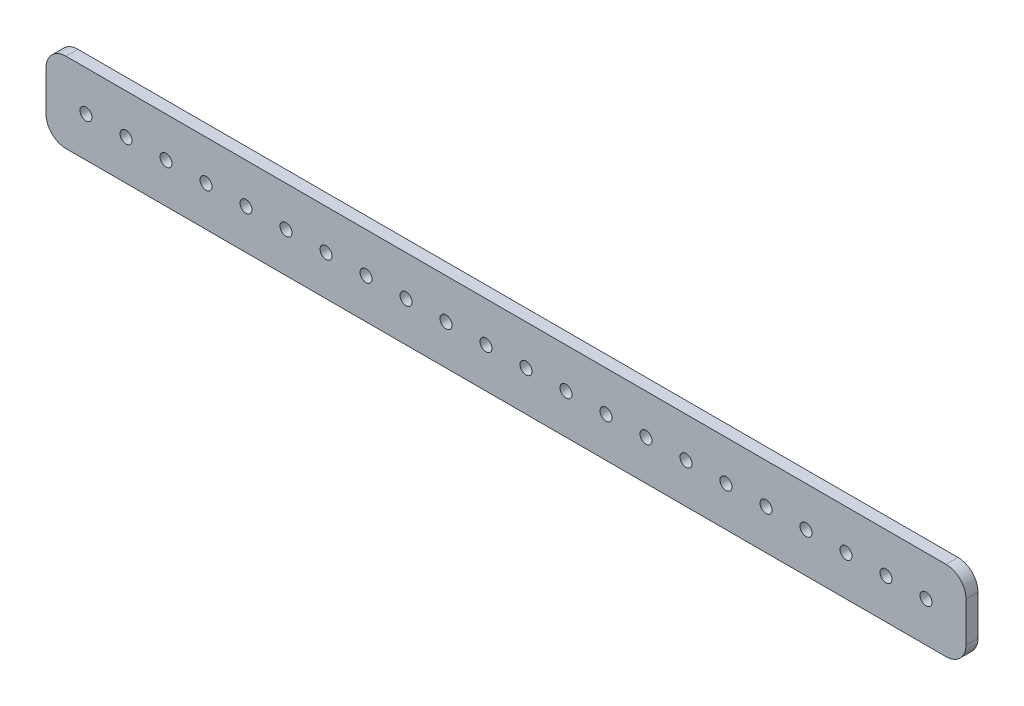
SolidWorks part; units mm, degrees
material "Maple"
ref_plane "Front Plane" through (0, 0, 0) normal (0, 0, 1) x (1, 0, 0)
ref_plane "Top Plane" through (0, 0, 0) normal (0, 1, 0) x (1, 0, 0)
ref_plane "Right Plane" through (0, 0, 0) normal (1, 0, 0) x (0, 0, -1)
sketch "Sketch1" plane through (0, 0, 0) normal (0, 0, 1) x (1, 0, 0)
  line L1 (-110, 10) -> (110, 10)
  line L2 (-115, 5) -> (-115, -5)
  line L3 (-110, -10) -> (110, -10)
  line L4 (115, 5) -> (115, -5)
  line L5 (-115, 10) -> (115, -10) construction
  line L6 (-115, -10) -> (115, 10) construction
  line L50 (-115, 0) -> (-105, 0) construction
  line L51 (-105, 0) -> (-95, 0) construction
  line L52 (-95, 0) -> (-85, 0) construction
  line L53 (-85, 0) -> (-75, 0) construction
  line L54 (-75, 0) -> (-65, 0) construction
  line L55 (-65, 0) -> (-55, 0) construction
  line L56 (-55, 0) -> (-45, 0) construction
  line L57 (-45, 0) -> (-35, 0) construction
  line L58 (-35, 0) -> (-25, 0) construction
  line L59 (-25, 0) -> (-15, 0) construction
  line L60 (-15, 0) -> (-5, 0) construction
  line L61 (-5, 0) -> (5, 0) construction
  line L62 (5, 0) -> (15, 0) construction
  line L63 (15, 0) -> (25, 0) construction
  line L64 (25, 0) -> (35, 0) construction
  line L65 (35, 0) -> (45, 0) construction
  line L66 (45, 0) -> (55, 0) construction
  line L67 (55, 0) -> (65, 0) construction
  line L68 (65, 0) -> (75, 0) construction
  line L69 (75, 0) -> (85, 0) construction
  line L70 (85, 0) -> (95, 0) construction
  line L71 (95, 0) -> (105, 0) construction
  arc A21 (115, -5) -> (110, -10) centre (110, -5) cw
  arc A22 (115, 5) -> (110, 10) centre (110, 5) ccw
  arc A23 (-110, -10) -> (-115, -5) centre (-110, -5) cw
  arc A24 (-110, 10) -> (-115, 5) centre (-110, 5) ccw
  circle A46 centre (-105, 0) radius 1.5
  circle A47 centre (-95, 0) radius 1.5
  circle A48 centre (-85, 0) radius 1.5
  circle A49 centre (-75, 0) radius 1.5
  circle A50 centre (-65, 0) radius 1.5
  circle A51 centre (-55, 0) radius 1.5
  circle A52 centre (-45, 0) radius 1.5
  circle A53 centre (-35, 0) radius 1.5
  circle A54 centre (-25, 0) radius 1.5
  circle A55 centre (-15, 0) radius 1.5
  circle A56 centre (-5, 0) radius 1.5
  circle A57 centre (15, 0) radius 1.5
  circle A58 centre (25, 0) radius 1.5
  circle A59 centre (5, 0) radius 1.5
  circle A60 centre (35, 0) radius 1.5
  circle A61 centre (45, 0) radius 1.5
  circle A62 centre (55, 0) radius 1.5
  circle A63 centre (65, 0) radius 1.5
  circle A64 centre (75, 0) radius 1.5
  circle A65 centre (85, 0) radius 1.5
  circle A66 centre (95, 0) radius 1.5
  circle A88 centre (105, 0) radius 1.5
  point P0 (0, 0)
  dimension "D3" = 5
  dimension "D5" = 3
  dimension "D1" = 20
  dimension "D2" = 230
  dimension "D6" = 10
  dimension "D7" = 10
extrude "Boss-Extrude1" add sketch "Sketch1" along normal blind 3
